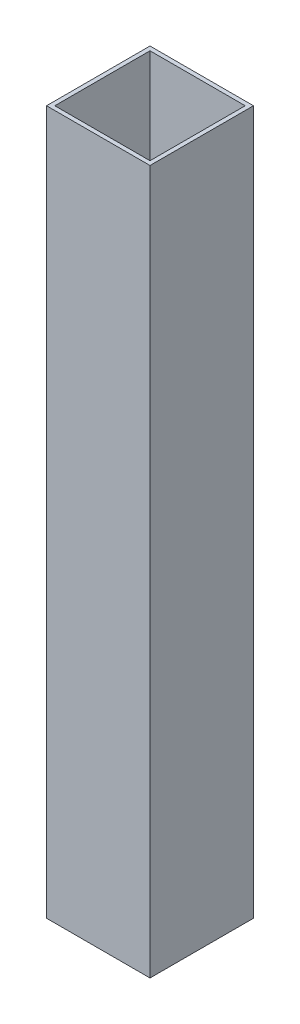
SolidWorks part; units mm, degrees
ref_plane "Front Plane" through (0, 0, 0) normal (0, 0, 1) x (1, 0, 0)
ref_plane "Top Plane" through (0, 0, 0) normal (0, 1, 0) x (1, 0, 0)
ref_plane "Right Plane" through (0, 0, 0) normal (1, 0, 0) x (0, 0, -1)
sketch "Sketch1" plane through (0, 0, 0) normal (0, 1, 0) x (1, 0, 0)
  line L0 (-23, 23) -> (23, 23)
  line L1 (-25, -25) -> (25, -25)
  line L2 (-25, -25) -> (-25, 25)
  line L3 (-25, 25) -> (25, 25)
  line L4 (25, -25) -> (25, 25)
  line L5 (-25, -25) -> (25, 25) construction
  line L6 (-25, 25) -> (25, -25) construction
  line L7 (23, -23) -> (23, 23)
  line L8 (-23, -23) -> (23, -23)
  line L9 (-23, -23) -> (-23, 23)
  point P0 (0, 0)
  dimension "D1" = 50
  dimension "D2" = 2
extrude "Boss-Extrude1" add sketch "Sketch1" along normal blind 340
